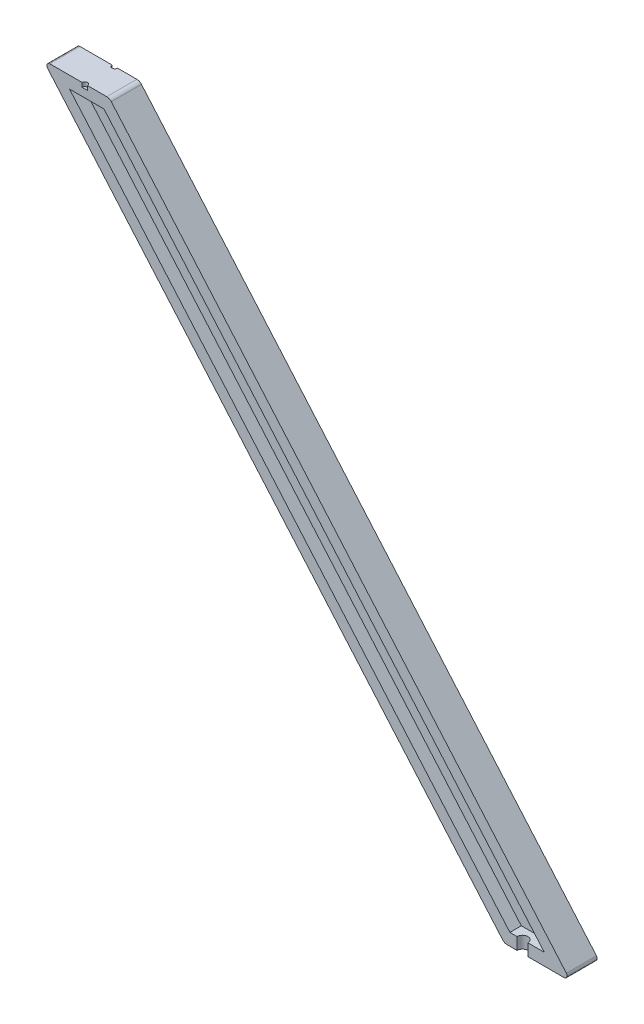
SolidWorks part; units mm, degrees
material "6061-T6 (SS)"
ref_plane "Front Plane" through (0, 0, 0) normal (0, 0, 1) x (1, 0, 0)
ref_plane "Top Plane" through (0, 0, 0) normal (0, 1, 0) x (1, 0, 0)
ref_plane "Right Plane" through (0, 0, 0) normal (1, 0, 0) x (0, 0, -1)
sketch "Sketch1" plane through (0, 0, 0) normal (0, 0, 1) x (1, 0, 0)
  line L0 (-0.7599, 0.8803) -> (-192.6595, 223.1982)
  line L1 (1.1629, 0) -> (25.1661, 0)
  line L2 (26.1275, 2.0998) -> (-165.7722, 224.4177)
  line L3 (-167.6949, 225.298) -> (-191.6981, 225.298)
  arc A0 (-192.6595, 223.1982) -> (-191.6981, 225.298) centre (-191.6981, 224.028) cw
  arc A1 (-165.7722, 224.4177) -> (-167.6949, 225.298) centre (-167.6949, 222.758) ccw
  arc A2 (25.1661, 0) -> (26.1275, 2.0998) centre (25.1661, 1.27) ccw
  arc A3 (1.1629, 0) -> (-0.7599, 0.8803) centre (1.1629, 2.54) cw
  point P7 (-194.472, 225.298)
  point P12 (27.94, 0)
  point P15 (0, 0)
  dimension "D4" = 2.54
  dimension "D5" = 1.27
  dimension "D6" = 1.27
  dimension "D7" = 2.54
  dimension "D1" = 225.298
  dimension "D2" = 27.94
  dimension "D3" = 49.2
extrude "Boss-Extrude1" add sketch "Sketch1" along normal blind 12.7
sketch "Sketch3" plane through (0, 0, 12.7) normal (0, 0, 1) x (1, 0, 0)
  line L0 (0, 0) -> (27.94, 0)
  line L5 (2.6445, 5.08) -> (18.1814, 5.08)
  line L8 (27.94, 0) -> (-132.1274, 228.6) construction
  line L9 (-132.1274, 228.6) -> (-160.0674, 228.6) construction
  line L10 (-160.0674, 228.6) -> (0, 0) construction
  line L11 (-150.3089, 223.52) -> (2.6445, 5.08) construction
  line L12 (18.1814, 5.08) -> (-134.7719, 223.52) construction
  line L13 (-134.7719, 223.52) -> (-150.3089, 223.52) construction
  line L31 (-183.3763, 220.218) -> (2.3258, 5.08)
  line L32 (2.3258, 5.08) -> (16.8443, 5.08)
  line L33 (16.8443, 5.08) -> (-168.8578, 220.218)
  line L34 (-168.8578, 220.218) -> (-183.3763, 220.218)
  line L35 (-183.3763, 220.218) -> (2.3258, 5.08)
  line L36 (2.3258, 5.08) -> (16.8443, 5.08)
  line L37 (16.8443, 5.08) -> (-168.8578, 220.218)
  line L38 (-168.8578, 220.218) -> (-183.3763, 220.218)
  dimension "D1" = 5.08
  dimension "D2" = 5.08
extrude "Cut-Extrude1" cut sketch "Sketch3" against normal blind 4.826
sketch "Sketch4" plane through (0, 0, 0) normal (0, 0, -1) x (-1, 0, 0)
  line L0 (-27.94, 0) -> (0, 0)
  line L7 (-18.1814, 5.08) -> (-2.6445, 5.08)
  line L8 (0, 0) -> (160.0674, 228.6) construction
  line L9 (160.0674, 228.6) -> (132.1274, 228.6) construction
  line L10 (132.1274, 228.6) -> (-27.94, 0) construction
  line L11 (-2.6445, 5.08) -> (150.3089, 223.52) construction
  line L12 (150.3089, 223.52) -> (134.7719, 223.52) construction
  line L13 (134.7719, 223.52) -> (-18.1814, 5.08) construction
  line L30 (183.3763, 220.218) -> (168.8578, 220.218)
  line L31 (168.8578, 220.218) -> (-16.8443, 5.08)
  line L32 (-16.8443, 5.08) -> (-2.3258, 5.08)
  line L33 (-2.3258, 5.08) -> (183.3763, 220.218)
  line L34 (183.3763, 220.218) -> (168.8578, 220.218)
  line L35 (168.8578, 220.218) -> (-16.8443, 5.08)
  line L36 (-16.8443, 5.08) -> (-2.3258, 5.08)
  line L37 (-2.3258, 5.08) -> (183.3763, 220.218)
  dimension "D1" = 5.08
  dimension "D2" = 5.08
extrude "Cut-Extrude2" cut sketch "Sketch4" against normal blind 4.826
sketch "Sketch5" plane through (0, 223.52, 0) normal (0, -1, 0) x (1, 0, 0)
  line L0 (-150.3089, 0) -> (-134.7719, 0) construction
  line L1 (-192.6595, 6.35) -> (26.4361, 6.35) construction
  line L2 (-192.6595, 12.7) -> (-192.6595, 0) construction
  line L3 (26.4361, 0) -> (26.4361, 12.7) construction
  circle A0 centre (-176.9482, 0) radius 1.143
  circle A1 centre (-176.9482, 12.7) radius 1.143
  dimension "D2" = 2.286
  dimension "D1" = 11.176
extrude "Cut-Extrude3" cut sketch "Sketch5" against normal through all
sketch "Sketch6" plane through (0, 5.08, 0) normal (0, 1, 0) x (1, 0, 0)
  line L1 (2.6445, -12.7) -> (18.1814, -12.7) construction
  line L2 (26.4361, -6.35) -> (-191.6981, -6.35) construction
  line L3 (26.4361, -12.7) -> (26.4361, 0) construction
  line L4 (-191.6981, -12.7) -> (-191.6981, 0) construction
  circle A1 centre (7.6221, -12.7) radius 2.286
  circle A2 centre (7.6221, 0) radius 2.286
  dimension "D1" = 8.382
  dimension "D2" = 4.572
extrude "Cut-Extrude4" cut sketch "Sketch6" against normal through all
